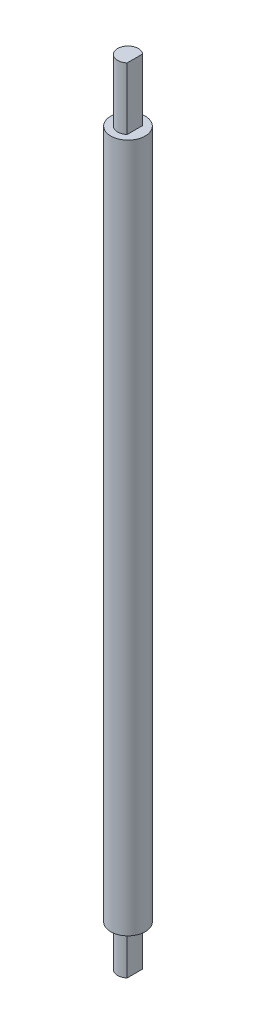
SolidWorks part; units mm, degrees
ref_plane "前视基准面" through (0, 0, 0) normal (0, 0, 1) x (1, 0, 0)
ref_plane "上视基准面" through (0, 0, 0) normal (0, 1, 0) x (1, 0, 0)
ref_plane "右视基准面" through (0, 0, 0) normal (1, 0, 0) x (0, 0, -1)
sketch "草图1" plane through (0, 0, 0) normal (0, 1, 0) x (1, 0, 0)
  circle A0 centre (0, 0) radius 2.5
extrude "凸台-拉伸1" add sketch "草图1" along normal blind 100
sketch "草图2" plane through (0, 100, 0) normal (0, 1, 0) x (1, 0, 0)
  line L0 (0, 0) -> (1, 0) construction
  line L1 (1, 1.118) -> (1, -1.118)
  arc A1 (1, -1.118) -> (1, 1.118) centre (0, 0) cw
extrude "凸台-拉伸2" add sketch "草图2" along normal blind 9
sketch "草图3" plane through (0, 0, 0) normal (0, -1, 0) x (1, 0, 0)
  line L0 (0, 0) -> (1, 0) construction
  line L1 (1, -1.118) -> (1, 1.118)
  arc A1 (1, -1.118) -> (1, 1.118) centre (0, 0) cw
extrude "凸台-拉伸3" add sketch "草图3" along normal blind 6
